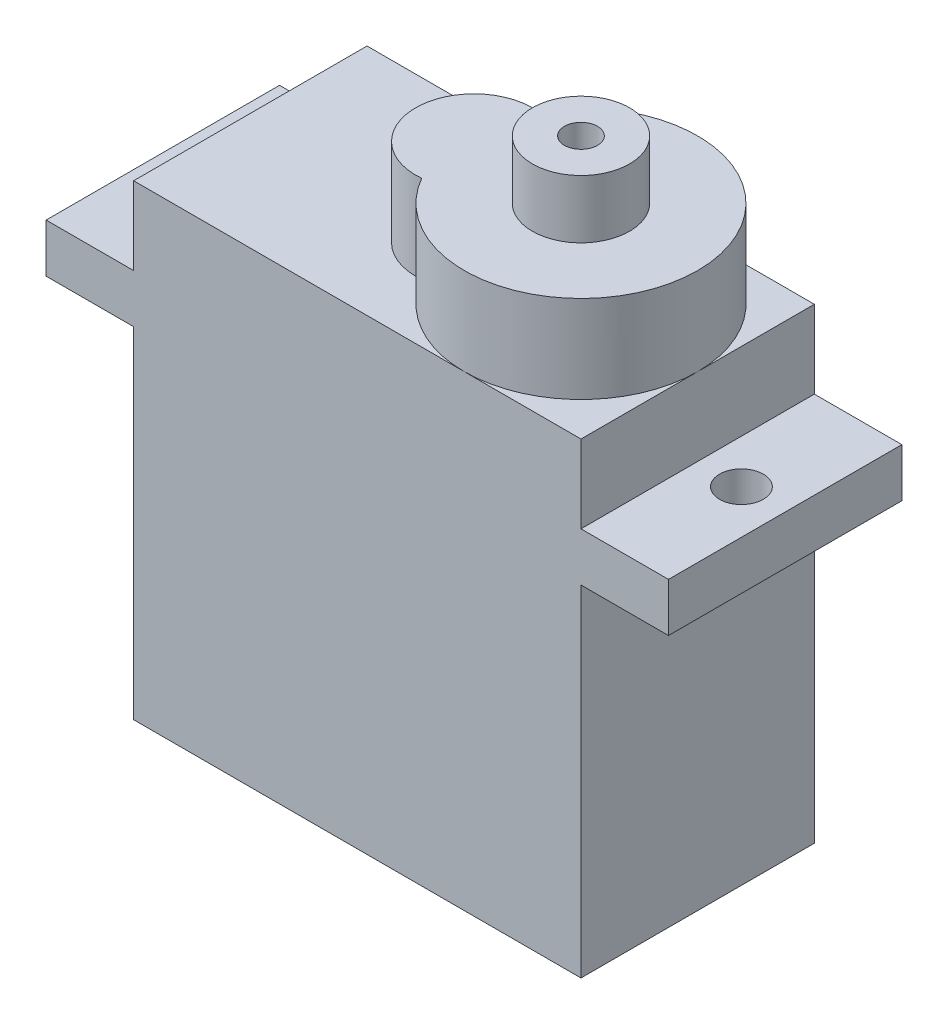
SolidWorks part; units mm, degrees
ref_plane "Front Plane" through (0, 0, 0) normal (0, 0, 1) x (1, 0, 0)
ref_plane "Top Plane" through (0, 0, 0) normal (0, 1, 0) x (1, 0, 0)
ref_plane "Right Plane" through (0, 0, 0) normal (1, 0, 0) x (0, 0, -1)
sketch "Sketch1" plane through (0, 0, 0) normal (0, 1, 0) x (1, 0, 0)
  line L1 (11.5, 6) -> (-11.5, 6)
  line L2 (11.5, 6) -> (11.5, -6)
  line L3 (11.5, -6) -> (-11.5, -6)
  line L4 (-11.5, 6) -> (-11.5, -6)
  line L5 (11.5, 6) -> (-11.5, -6) construction
  line L6 (11.5, -6) -> (-11.5, 6) construction
  point P0 (0, 0)
  dimension "D1" = 23
  dimension "D2" = 12
extrude "Boss-Extrude1" add sketch "Sketch1" along normal blind 24
sketch "Sketch2" plane through (0, 24, 0) normal (0, 1, 0) x (1, 0, 0)
  line L1 (11.5, 6) -> (-11.5, 6) construction
  line L3 (11.5, -6) -> (11.5, 6) construction
  line L4 (0, 0) -> (11.5, 0) construction
  arc A0 (0.2955, 2.9854) -> (0.2955, -2.9854) centre (0, 0) ccw
  arc A1 (0.2955, -2.9854) -> (0.2955, 2.9854) centre (5.5, 0) ccw
  dimension "D2" = 6
extrude "Boss-Extrude2" add sketch "Sketch2" along normal blind 4.5
sketch "Sketch3" plane through (0, 28.5, 0) normal (0, 1, 0) x (1, 0, 0)
  circle A0 centre (5.5, 0) radius 2.5
  dimension "D1" = 5
extrude "Boss-Extrude3" add sketch "Sketch3" along normal blind 3
sketch "Sketch4" plane through (0, 31.5, 0) normal (0, 1, 0) x (1, 0, 0)
  circle A0 centre (5.5, 0) radius 0.85
  dimension "D1" = 1.7
extrude "Cut-Extrude1" cut sketch "Sketch4" against normal blind 5
sketch "Sketch5" plane through (0, 24, 0) normal (0, 1, 0) x (1, 0, 0)
  line L0 (-16, 0) -> (-11.5, 0) construction
  line L1 (-11.5, 6) -> (-16, 6)
  line L2 (-11.5, 6) -> (-11.5, -6)
  line L3 (-11.5, -6) -> (-16, -6)
  line L4 (-16, 6) -> (-16, -6)
  line L5 (0, 0) -> (0, -8.2379) construction
  line L6 (16, 0) -> (11.5, 0) construction
  line L7 (16, 6) -> (16, -6)
  line L8 (11.5, -6) -> (16, -6)
  line L9 (11.5, 6) -> (11.5, -6)
  line L10 (11.5, 6) -> (16, 6)
  circle A0 centre (-13.75, 0) radius 1.125
  circle A1 centre (13.75, 0) radius 1.125
  dimension "D2" = 2.25
  dimension "D1" = 4.5
extrude "Boss-Extrude4" add sketch "Sketch5" against normal blind 2.5 from offset 4
